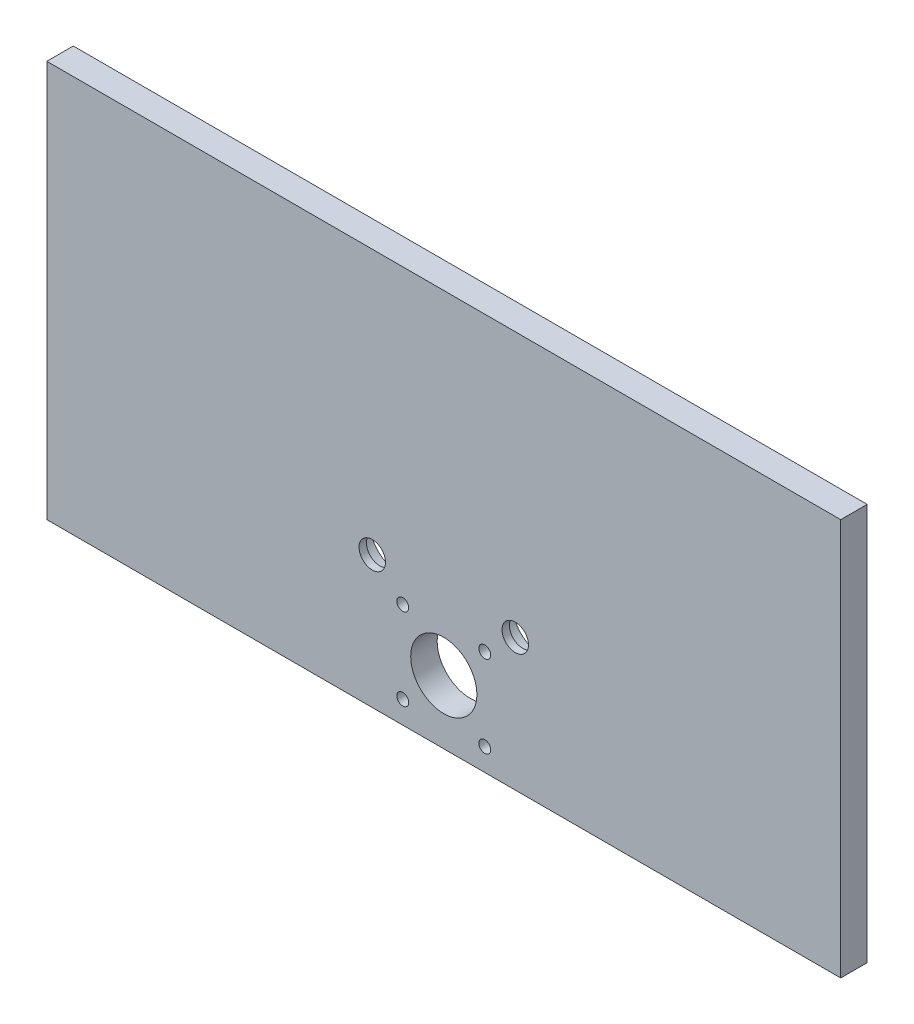
SolidWorks part; units mm, degrees
ref_plane "Front" through (0, 0, 0) normal (0, 0, 1) x (1, 0, 0)
ref_plane "Top" through (0, 0, 0) normal (0, 1, 0) x (1, 0, 0)
ref_plane "Right" through (0, 0, 0) normal (1, 0, 0) x (0, 0, -1)
sketch "Sketch1" plane through (0, 0, 0) normal (0, 0, 1) x (1, 0, 0)
  line L1 (-150, -75) -> (150, -75)
  line L2 (-150, -75) -> (-150, 75)
  line L3 (-150, 75) -> (150, 75)
  line L4 (150, -75) -> (150, 75)
  line L5 (-150, -75) -> (150, 75) construction
  line L6 (-150, 75) -> (150, -75) construction
  point P0 (0, 0)
  dimension "D1" = 300
  dimension "D2" = 150
extrude "Boss-Extrude1" add sketch "Sketch1" along normal blind 10
sketch "Sketch2" plane through (0, 0, 0) normal (0, 0, -1) x (-1, 0, 0)
  line L0 (150, -75) -> (-150, -75) construction
  circle A0 centre (0, -51) radius 12.5
  dimension "D1" = 25
  dimension "D2" = 24
extrude "Cut-Extrude1" cut sketch "Sketch2" against normal through all
hole_wizard "M4 Clearance Hole1" positions "Sketch4" profile "Sketch3" hole size "M4" standard "ANSI Metric"
sketch "Sketch4" plane through (0, 0, 10) normal (0, 0, 1) x (1, 0, 0)
  line L1 (-15.5, -66.5) -> (15.5, -66.5) construction
  line L2 (-15.5, -66.5) -> (-15.5, -35.5) construction
  line L3 (-15.5, -35.5) -> (15.5, -35.5) construction
  line L4 (15.5, -66.5) -> (15.5, -35.5) construction
  line L5 (15.5, -35.5) -> (-15.5, -66.5) construction
  line L8 (-15.5, -51) -> (15.5, -51) construction
  line L11 (-150, -75) -> (150, -75) construction
  point P0 (-15.5, -35.5)
  point P2 (15.5, -35.5)
  point P4 (15.5, -66.5)
  point P6 (-15.5, -66.5)
  point P188 (0, -51)
  dimension "D1" = 31
  dimension "D2" = 31
  dimension "D3" = 24
sketch "Sketch3" plane through (-15.5, -35.5, 10) normal (1, 0, 0) x (0, -1, 0)
  line L0 (0, 0) -> (0, 22.3519)
  line L1 (0, 22.3519) -> (2.25, 21)
  line L2 (2.25, 21) -> (2.25, 0)
  line L5 (2.25, 0) -> (0, 0)
  line L10 (0, 22.3519) -> (-2.25, 21) construction
  line L11 (0, -6.35) -> (0, 107.95) construction
  dimension "Hole Dia." = 4.5
  dimension "Hole Depth" = 21
  dimension "Drill Angle" = 118
sketch "Sketch5" plane through (0, 0, 10) normal (0, 0, 1) x (1, 0, 0)
  circle A0 centre (27.0137, -25) radius 19.05 construction
  circle A1 centre (27.0137, -25) radius 5
  circle A3 centre (0, -51) radius 18.4432 construction
  dimension "D1" = 38.1
  dimension "D2" = 25
  dimension "D3" = 10
extrude "Cut-Extrude2" cut sketch "Sketch5" against normal through all
mirror "Mirror1" about plane through (0, 0, 0) normal (1, 0, 0) of "Cut-Extrude2"
sketch "Sketch6" plane through (0, 0, 0) normal (0, 0, -1) x (-1, 0, 0)
  circle A0 centre (-27.0137, -25) radius 11
  circle A1 centre (27.0137, -25) radius 11
  dimension "D1" = 22
extrude "Cut-Extrude3" cut sketch "Sketch6" against normal blind 7.2
